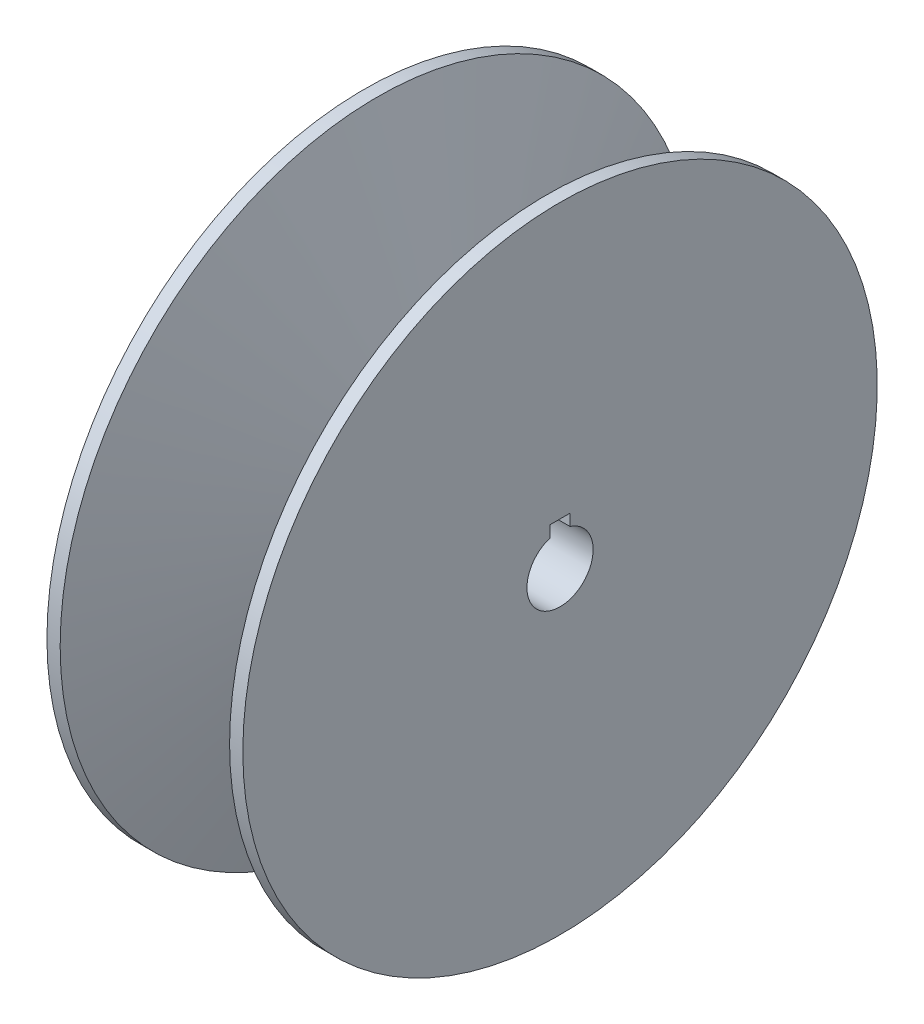
SolidWorks part; units mm, degrees
material "Plain Carbon Steel"
ref_plane "Front Plane" through (0, 0, 0) normal (0, 0, 1) x (1, 0, 0)
ref_plane "Top Plane" through (0, 0, 0) normal (0, 1, 0) x (1, 0, 0)
ref_plane "Right Plane" through (0, 0, 0) normal (1, 0, 0) x (0, 0, -1)
sketch "Sketch1" plane through (0, 0, 0) normal (0, 0, 1) x (1, 0, 0)
  line L0 (0, 0) -> (40.64, 0) construction
  line L1 (0, 0) -> (0, 76.0921) construction
  line L2 (40.64, 0) -> (40.64, 76.0921) construction
  line L3 (0, 76.0921) -> (40.64, 76.0921) construction
  line L4 (20.32, 76.0921) -> (20.32, 8.9982) construction
  line L5 (40.64, 6.35) -> (-40.64, 6.35) construction
  line L6 (0, 76.0921) -> (18.6267, 12.7)
  line L7 (40.64, 76.0921) -> (22.0133, 12.7)
  line L8 (13.2385, 31.0377) -> (27.4015, 31.0377)
  line L9 (0, 76.0921) -> (0, 6.35)
  line L10 (0, 6.35) -> (22.0133, 6.35)
  line L11 (22.0133, 12.7) -> (40.64, 12.7) construction
  line L12 (22.0133, 6.35) -> (40.64, 6.35)
  line L13 (40.64, 6.35) -> (40.64, 76.0921)
  line L14 (0, 76.0921) -> (-3.175, 76.0921)
  line L15 (-3.175, 76.0921) -> (-3.175, 6.35)
  line L16 (-3.175, 6.35) -> (0, 6.35)
  line L18 (40.64, 76.0921) -> (43.815, 76.0921)
  line L19 (40.64, 76.0921) -> (40.64, 6.35)
  line L20 (40.64, 6.35) -> (43.815, 6.35)
  line L21 (43.815, 76.0921) -> (43.815, 6.35)
  dimension "D1" = 3.175
  dimension "D2" = 40.64
  dimension "D3" = 76.0921
  dimension "D4" = 3.175
  dimension "D5" = 6.35
revolve "Revolve1" add sketch "Sketch1" angle 360 about L0
sketch "Sketch2" plane through (43.815, 0, 0) normal (1, 0, 0) x (0, 0, -1)
  line L0 (0, 0) -> (0, 7.9375) construction
  line L2 (2.3812, 5.5563) -> (-2.3813, 5.5562)
  line L3 (2.3812, 5.5563) -> (2.3812, 10.3188)
  line L4 (2.3812, 10.3188) -> (-2.3813, 10.3188)
  line L5 (-2.3813, 5.5562) -> (-2.3813, 10.3188)
  line L6 (2.3812, 5.5563) -> (-2.3813, 10.3188) construction
  line L7 (2.3812, 10.3188) -> (-2.3813, 5.5562) construction
  circle A0 centre (0, 0) radius 7.9375
  dimension "D1" = 15.875
  dimension "D2" = 4.7625
  dimension "D3" = 4.7625
extrude "Cut-Extrude1" cut sketch "Sketch2" against normal blind 108.204 and the other way blind 25.146
ref_plane "Plane1" through (20.32, 0, 0) normal (-1, 0, 0) x (0, 0, 1)
